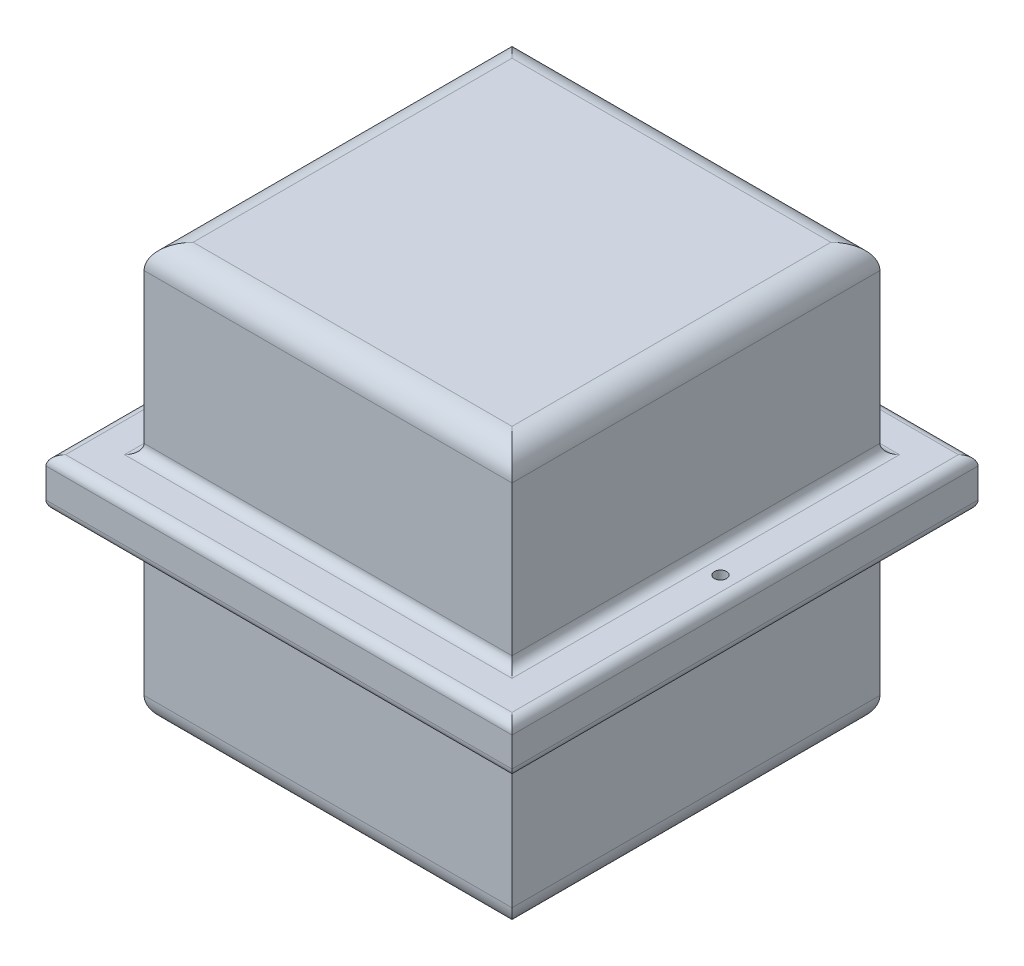
SolidWorks part; units mm, degrees
ref_plane "Front Plane" through (0, 0, 0) normal (0, 0, 1) x (1, 0, 0)
ref_plane "Top Plane" through (0, 0, 0) normal (0, 1, 0) x (1, 0, 0)
ref_plane "Right Plane" through (0, 0, 0) normal (1, 0, 0) x (0, 0, -1)
sketch "Sketch1" plane through (0, 0, 0) normal (0, 1, 0) x (1, 0, 0)
  line L1 (0, 0) -> (19.05, 0)
  line L2 (0, 0) -> (0, 19.05)
  line L3 (0, 19.05) -> (19.05, 19.05)
  line L4 (19.05, 0) -> (19.05, 19.05)
  dimension "D1" = 19.05
  dimension "D2" = 19.05
extrude "Boss-Extrude1" add sketch "Sketch1" along normal blind 9.525
fillet "Fillet1" radius 1.27 4 edges at (0, 9.525, -9.525) (9.525, 9.525, -19.05) (19.05, 9.525, -9.525) (9.525, 9.525, 0)
sketch "Sketch2" plane through (0, 0, 0) normal (0, -1, 0) x (1, 0, 0)
  line L23 (-2.54, -21.59) -> (21.59, -21.59)
  line L24 (21.59, -21.59) -> (21.59, 2.54)
  line L25 (-2.54, 2.54) -> (-2.54, -21.59)
  line L26 (21.59, 2.54) -> (-2.54, 2.54)
  line L27 (-2.54, -21.59) -> (21.59, -21.59)
  line L28 (21.59, -21.59) -> (21.59, 2.54)
  line L29 (-2.54, 2.54) -> (-2.54, -21.59)
  line L30 (21.59, 2.54) -> (-2.54, 2.54)
  dimension "D1" = 2.54
extrude "Boss-Extrude2" add sketch "Sketch2" along normal blind 1.27 contours L30 L29 L27 L28
fillet "Fillet2" radius 0.508 8 edges at (21.59, 0, -9.525) (9.525, 0, -21.59) (-2.54, 0, -9.525) (9.525, 0, 2.54) (9.525, 0, 0) (0, 0, -9.525) (19.05, 0, -9.525) (9.525, 0, -19.05)
sketch "Sketch3" plane through (0, -1.27, 0) normal (0, -1, 0) x (1, 0, 0)
  line L0 (19.05, 0) -> (19.05, -19.05) construction
  line L1 (19.05, -19.05) -> (0, -19.05) construction
  line L2 (0, 0) -> (19.05, 0) construction
  line L3 (0, -19.05) -> (0, 0) construction
  line L4 (21.59, -21.59) -> (21.59, 2.54)
  line L5 (21.59, 2.54) -> (-2.54, 2.54)
  line L6 (-2.54, 2.54) -> (-2.54, -21.59)
  line L7 (-2.54, -21.59) -> (21.59, -21.59)
  line L8 (21.59, -21.59) -> (21.59, 2.54)
  line L9 (21.59, 2.54) -> (-2.54, 2.54)
  line L10 (-2.54, 2.54) -> (-2.54, -21.59)
  line L11 (-2.54, -21.59) -> (21.59, -21.59)
  line L12 (19.05, 0) -> (19.05, -19.05)
  line L13 (19.05, -19.05) -> (0, -19.05)
  line L14 (0, 0) -> (19.05, 0)
  line L15 (0, -19.05) -> (0, 0)
  line L16 (1.27, -1.27) -> (17.78, -1.27)
  line L17 (17.78, -1.27) -> (17.78, -17.78)
  line L18 (17.78, -17.78) -> (1.27, -17.78)
  line L19 (1.27, -17.78) -> (1.27, -1.27)
  dimension "D1" = 0
  dimension "D2" = 1.27
extrude "Cut-Extrude2" cut sketch "Sketch3" against normal blind 8.89 contours L16 L17 L18 L19
mirror "Mirror3" about plane through (0, -1.27, 0) normal (0, -1, 0) of bodies 103
sketch "Sketch4" plane through (0, 0, 0) normal (0, 1, 0) x (1, 0, 0)
  line L0 (-2.032, 21.082) -> (21.082, -2.032) construction
  line L1 (21.59, 9.525) -> (19.05, 9.525) construction
  line L2 (19.05, 0) -> (19.05, 19.05) construction
  line L3 (21.082, 21.082) -> (-2.032, -2.032) construction
  line L4 (9.525, 9.525) -> (9.525, 22.6275) construction
  line L5 (9.525, 9.525) -> (-5.113, 9.525) construction
  circle A0 centre (20.32, 9.525) radius 0.3175
  circle A1 centre (-1.27, 9.525) radius 0.3175
  dimension "D1" = 0.635
extrude "Cut-Extrude3" cut sketch "Sketch4" against normal through all contours A1 | A0
